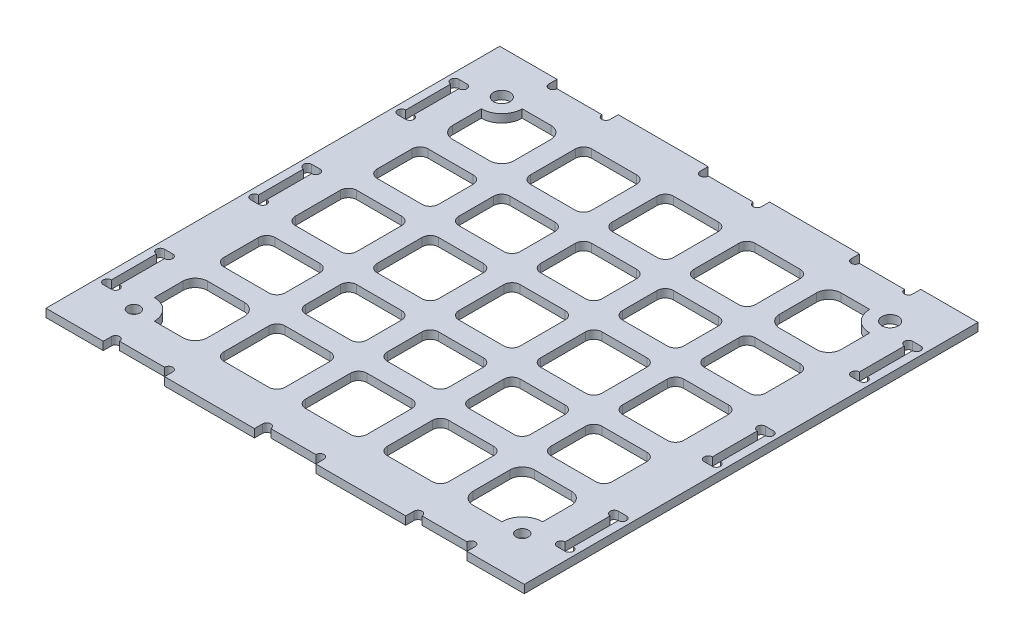
SolidWorks part; units mm, degrees
ref_plane "前视基准面" through (0, 0, 0) normal (0, 0, 1) x (1, 0, 0)
ref_plane "上视基准面" through (0, 0, 0) normal (0, 1, 0) x (1, 0, 0)
ref_plane "右视基准面" through (0, 0, 0) normal (1, 0, 0) x (0, 0, -1)
sketch "草图1" plane through (0, 0, 0) normal (0, 1, 0) x (1, 0, 0)
  line L0 (53, 107) -> (53, 47) construction
  line L1 (0, 0) -> (109, 0)
  line L2 (0, 0) -> (0, 107)
  line L3 (0, 107) -> (109, 107)
  line L4 (109, 0) -> (109, 107)
  line L6 (7, 98.5) -> (102, 98.5) construction
  line L7 (7, 98.5) -> (7, 8.5) construction
  line L8 (7, 8.5) -> (102, 8.5) construction
  line L9 (102, 98.5) -> (102, 8.5) construction
  circle A20 centre (7, 98.5) radius 2
  circle A21 centre (102, 98.5) radius 2
  circle A22 centre (102, 8.5) radius 1.5
  circle A23 centre (7, 8.5) radius 1.5
  dimension "D5" = 107
  dimension "D13" = 4
  dimension "D14" = 4
  dimension "D15" = 3
  dimension "D16" = 3
  dimension "D2" = 109
  dimension "D3" = 60
  dimension "D4" = 53
  dimension "D9" = 90
  dimension "D10" = 95
  dimension "D11" = 8.5
  dimension "D12" = 7
extrude "凸台-拉伸1" add sketch "草图1" along normal blind 2
sketch "草图2" plane through (0, 2, 0) normal (0, 1, 0) x (1, 0, 0)
  line L0 (109, 107) -> (0, 107) construction
  line L5 (0, 0) -> (109, 0) construction
  line L6 (0, 107) -> (0, 0) construction
  line L7 (109, 0) -> (109, 107) construction
  line L9 (10, 107) -> (10, 109)
  line L11 (25, 107) -> (25, 109)
  line L13 (47, 107) -> (47, 109)
  line L15 (62, 107) -> (62, 109)
  line L17 (84, 107) -> (84, 109)
  line L19 (99, 107) -> (99, 109)
  line L20 (0, 53.5) -> (109, 53.5) construction
  line L21 (54.5, 0) -> (54.5, 107) construction
  line L22 (109, 97) -> (111, 97)
  line L48 (0, 97) -> (-2, 97)
  line L49 (10, 107) -> (0, 107)
  line L50 (0, 107) -> (0, 97)
  line L51 (25, 107) -> (47, 107)
  line L52 (62, 107) -> (84, 107)
  line L53 (99, 107) -> (109, 107)
  line L54 (109, 107) -> (109, 97)
  line L67 (10, 109) -> (-2, 109)
  line L68 (-2, 109) -> (-2, 97)
  line L69 (25, 109) -> (47, 109)
  line L70 (62, 109) -> (84, 109)
  line L71 (99, 109) -> (111, 109)
  line L72 (111, 109) -> (111, 97)
  line L81 (109, 82) -> (111, 82) [skipped]
  line L82 (109, 60) -> (111, 60) [skipped]
  line L83 (109, 45) -> (111, 45) [skipped]
  line L84 (109, 23) -> (111, 23) [skipped]
  line L85 (109, 8) -> (111, 8) [skipped]
  line L86 (99, -2) -> (99, -4) [skipped]
  line L87 (84, -2) -> (84, -4) [skipped]
  line L88 (62, -2) -> (62, -4) [skipped]
  line L89 (47, -2) -> (47, -4) [skipped]
  line L90 (25, -2) -> (25, -4) [skipped]
  line L91 (10, -2) -> (10, -4) [skipped]
  line L92 (0, 8) -> (-2, 8) [skipped]
  line L93 (0, 23) -> (-2, 23) [skipped]
  line L94 (0, 45) -> (-2, 45) [skipped]
  line L95 (0, 60) -> (-2, 60) [skipped]
  line L96 (0, 82) -> (-2, 82) [skipped]
  line L97 (111, 46) -> (111, 25)
  line L98 (0, 82) -> (-2, 82)
  line L99 (0, 82) -> (0, 61)
  line L100 (0, 61) -> (-2, 61)
  line L101 (-2, 82) -> (-2, 61)
  line L102 (0, 46) -> (-2, 46)
  line L103 (0, 46) -> (0, 25)
  line L104 (0, 25) -> (-2, 25)
  line L105 (-2, 46) -> (-2, 25)
  line L106 (109, 25) -> (111, 25)
  line L107 (109, 46) -> (109, 25)
  line L108 (109, 46) -> (111, 46)
  line L109 (111, 82) -> (111, 61)
  line L110 (109, 61) -> (111, 61)
  line L111 (109, 82) -> (109, 61)
  line L112 (109, 82) -> (111, 82)
  line L113 (111, -2) -> (111, 10)
  line L114 (99, -2) -> (111, -2)
  line L115 (62, -2) -> (84, -2)
  line L116 (25, -2) -> (47, -2)
  line L117 (-2, -2) -> (-2, 10)
  line L118 (10, -2) -> (-2, -2)
  line L119 (109, 0) -> (109, 10)
  line L120 (99, 0) -> (109, 0)
  line L121 (62, 0) -> (84, 0)
  line L122 (25, 0) -> (47, 0)
  line L123 (0, 0) -> (0, 10)
  line L124 (10, 0) -> (0, 0)
  line L125 (0, 10) -> (-2, 10)
  line L126 (109, 10) -> (111, 10)
  line L127 (99, 0) -> (99, -2)
  line L128 (84, 0) -> (84, -2)
  line L129 (62, 0) -> (62, -2)
  line L130 (47, 0) -> (47, -2)
  line L131 (25, 0) -> (25, -2)
  line L132 (10, 0) -> (10, -2)
  dimension "D2" = 22
  dimension "D3" = 15
  dimension "D4" = 10
  dimension "D5" = 15
  dimension "D6" = 21
  dimension "D7" = 15
  dimension "D8" = 10
  dimension "D9" = 15
  dimension "D10" = 2
  dimension "D12" = 15
  dimension "D13" = 21
  dimension "D11" = 4
extrude "凸台-拉伸2" add sketch "草图2" against normal up to surface (2 mm away) up to face at (102, 0, -7)
sketch "草图4" plane through (0, 2, 0) normal (0, 1, 0) x (1, 0, 0)
  line L0 (25, 107) -> (10, 107) construction
  line L1 (10, 107) -> (12, 107)
  line L2 (17.5, 107) -> (17.5, 0) construction
  line L4 (36, 109) -> (36, -2) construction
  line L5 (0, 53.5) -> (109, 53.5) construction
  line L6 (47, 109) -> (25, 109) construction
  line L8 (54.5, 107) -> (54.5, 0) construction
  line L9 (62, 107) -> (47, 107) construction
  line L11 (25, 107) -> (23, 107)
  line L12 (47, 107) -> (49, 107)
  line L13 (62, 107) -> (60, 107)
  line L14 (84, 107) -> (86, 107)
  line L15 (99, 107) -> (97, 107)
  line L34 (0, 84) -> (0, 82)
  line L35 (0, 61) -> (0, 46) construction
  line L36 (109, 46) -> (109, 61) construction
  line L37 (99, 0) -> (97, 0)
  line L38 (84, 0) -> (86, 0)
  line L39 (62, 0) -> (60, 0)
  line L40 (47, 0) -> (49, 0)
  line L41 (25, 0) -> (23, 0)
  line L42 (10, 0) -> (12, 0)
  line L43 (0, 95) -> (0, 97)
  line L44 (0, 97) -> (0, 82) construction
  line L45 (0, 89.5) -> (109, 89.5) construction
  line L46 (109, 82) -> (109, 97) construction
  line L47 (-2, 71.5) -> (111, 71.5) construction
  line L48 (-2, 82) -> (-2, 61) construction
  line L49 (111, 61) -> (111, 82) construction
  line L50 (0, 59) -> (0, 61)
  line L51 (0, 48) -> (0, 46)
  line L52 (0, 12) -> (0, 10)
  line L53 (0, 23) -> (0, 25)
  line L54 (109, 23) -> (109, 25)
  line L55 (109, 12) -> (109, 10)
  line L56 (109, 48) -> (109, 46)
  line L57 (109, 59) -> (109, 61)
  line L58 (109, 95) -> (109, 97)
  line L59 (109, 84) -> (109, 82)
  line L60 (10, 0) -> (25, 0) construction
  line L61 (25, -2) -> (47, -2) construction
  line L62 (47, 0) -> (62, 0) construction
  arc A0 (10, 107) -> (12, 107) centre (11, 107) ccw
  arc A1 (99, 0) -> (97, 0) centre (98, 0) ccw
  arc A2 (25, 107) -> (23, 107) centre (24, 107) cw
  arc A3 (47, 107) -> (49, 107) centre (48, 107) ccw
  arc A4 (62, 107) -> (60, 107) centre (61, 107) cw
  arc A5 (84, 107) -> (86, 107) centre (85, 107) ccw
  arc A6 (99, 107) -> (97, 107) centre (98, 107) cw
  arc A25 (84, 0) -> (86, 0) centre (85, 0) cw
  arc A26 (62, 0) -> (60, 0) centre (61, 0) ccw
  arc A27 (47, 0) -> (49, 0) centre (48, 0) cw
  arc A28 (25, 0) -> (23, 0) centre (24, 0) ccw
  arc A29 (10, 0) -> (12, 0) centre (11, 0) cw
  arc A30 (0, 97) -> (0, 95) centre (0, 96) cw
  arc A31 (0, 82) -> (0, 84) centre (0, 83) ccw
  arc A32 (0, 61) -> (0, 59) centre (0, 60) cw
  arc A33 (0, 46) -> (0, 48) centre (0, 47) ccw
  arc A34 (0, 25) -> (0, 23) centre (0, 24) cw
  arc A35 (0, 10) -> (0, 12) centre (0, 11) ccw
  arc A36 (109, 10) -> (109, 12) centre (109, 11) cw
  arc A37 (109, 25) -> (109, 23) centre (109, 24) ccw
  arc A38 (109, 46) -> (109, 48) centre (109, 47) cw
  arc A39 (109, 61) -> (109, 59) centre (109, 60) ccw
  arc A40 (109, 82) -> (109, 84) centre (109, 83) cw
  arc A41 (109, 97) -> (109, 95) centre (109, 96) ccw
  dimension "D1" = 1
extrude "切除-拉伸1" cut sketch "草图4" against normal through all
sketch "草图5" plane through (0, 2, 0) normal (0, 1, 0) x (1, 0, 0)
  line L0 (12, 98.5) -> (19, 98.5)
  line L1 (22, 95.5) -> (22, 86.5)
  line L2 (19, 83.5) -> (10, 83.5)
  line L3 (7, 86.5) -> (7, 93.5)
  line L4 (0, 53.5) -> (109, 53.5) construction
  line L5 (0, 59) -> (0, 48) construction
  line L6 (109, 48) -> (109, 59) construction
  line L7 (54.5, 107) -> (54.5, 0) construction
  line L8 (60, 107) -> (49, 107) construction
  line L9 (49, 0) -> (60, 0) construction
  line L22 (102, 86.5) -> (102, 93.5)
  line L23 (90, 83.5) -> (99, 83.5)
  line L24 (87, 95.5) -> (87, 86.5)
  line L25 (97, 98.5) -> (90, 98.5)
  line L26 (97, 8.5) -> (90, 8.5)
  line L27 (87, 11.5) -> (87, 20.5)
  line L28 (90, 23.5) -> (99, 23.5)
  line L29 (102, 20.5) -> (102, 13.5)
  line L30 (7, 20.5) -> (7, 13.5)
  line L31 (19, 23.5) -> (10, 23.5)
  line L32 (22, 11.5) -> (22, 20.5)
  line L33 (12, 8.5) -> (19, 8.5)
  line L34 (80, 46) -> (69, 46)
  line L35 (9, 78.5) -> (20, 78.5)
  line L36 (7, 76.5) -> (7, 68)
  line L37 (9, 66) -> (20, 66)
  line L38 (22, 76.5) -> (22, 68)
  line L39 (9, 61) -> (20, 61)
  line L40 (7, 59) -> (7, 48)
  line L41 (9, 46) -> (20, 46)
  line L42 (22, 59) -> (22, 48)
  line L43 (29, 78.5) -> (40, 78.5)
  line L44 (27, 76.5) -> (27, 68)
  line L45 (29, 66) -> (40, 66)
  line L46 (42, 76.5) -> (42, 68)
  line L47 (29, 98.5) -> (40, 98.5)
  line L48 (27, 96.5) -> (27, 85.5)
  line L49 (29, 83.5) -> (40, 83.5)
  line L50 (42, 96.5) -> (42, 85.5)
  line L51 (49, 98.5) -> (60, 98.5)
  line L52 (47, 96.5) -> (47, 85.5)
  line L53 (49, 83.5) -> (60, 83.5)
  line L54 (62, 96.5) -> (62, 85.5)
  line L55 (49, 78.5) -> (60, 78.5)
  line L56 (47, 76.5) -> (47, 68)
  line L57 (49, 66) -> (60, 66)
  line L58 (62, 76.5) -> (62, 68)
  line L59 (29, 61) -> (40, 61)
  line L60 (27, 59) -> (27, 48)
  line L61 (29, 46) -> (40, 46)
  line L62 (42, 59) -> (42, 48)
  line L63 (49, 61) -> (60, 61)
  line L64 (47, 59) -> (47, 48)
  line L65 (49, 46) -> (60, 46)
  line L66 (62, 59) -> (62, 48)
  line L67 (67, 59) -> (67, 48)
  line L68 (80, 61) -> (69, 61)
  line L69 (82, 59) -> (82, 48)
  line L70 (100, 46) -> (89, 46)
  line L71 (87, 59) -> (87, 48)
  line L72 (100, 61) -> (89, 61)
  line L73 (102, 59) -> (102, 48)
  line L74 (100, 66) -> (89, 66)
  line L75 (87, 76.5) -> (87, 68)
  line L76 (100, 78.5) -> (89, 78.5)
  line L77 (102, 76.5) -> (102, 68)
  line L78 (80, 66) -> (69, 66)
  line L79 (67, 76.5) -> (67, 68)
  line L80 (80, 78.5) -> (69, 78.5)
  line L81 (82, 76.5) -> (82, 68)
  line L82 (80, 83.5) -> (69, 83.5)
  line L83 (67, 96.5) -> (67, 85.5)
  line L84 (80, 98.5) -> (69, 98.5)
  line L85 (82, 96.5) -> (82, 85.5)
  line L86 (102, 30.5) -> (102, 39)
  line L87 (100, 28.5) -> (89, 28.5)
  line L88 (87, 30.5) -> (87, 39)
  line L89 (100, 41) -> (89, 41)
  line L90 (82, 10.5) -> (82, 21.5)
  line L91 (80, 8.5) -> (69, 8.5)
  line L92 (67, 10.5) -> (67, 21.5)
  line L93 (80, 23.5) -> (69, 23.5)
  line L94 (82, 30.5) -> (82, 39)
  line L95 (80, 28.5) -> (69, 28.5)
  line L96 (67, 30.5) -> (67, 39)
  line L97 (80, 41) -> (69, 41)
  line L98 (49, 41) -> (60, 41)
  line L99 (62, 30.5) -> (62, 39)
  line L100 (49, 28.5) -> (60, 28.5)
  line L101 (47, 30.5) -> (47, 39)
  line L102 (49, 23.5) -> (60, 23.5)
  line L103 (62, 10.5) -> (62, 21.5)
  line L104 (49, 8.5) -> (60, 8.5)
  line L105 (47, 10.5) -> (47, 21.5)
  line L106 (29, 23.5) -> (40, 23.5)
  line L107 (42, 10.5) -> (42, 21.5)
  line L108 (29, 8.5) -> (40, 8.5)
  line L109 (27, 10.5) -> (27, 21.5)
  line L110 (29, 41) -> (40, 41)
  line L111 (42, 30.5) -> (42, 39)
  line L112 (29, 28.5) -> (40, 28.5)
  line L113 (27, 30.5) -> (27, 39)
  line L114 (9, 41) -> (20, 41)
  line L115 (22, 30.5) -> (22, 39)
  line L116 (9, 28.5) -> (20, 28.5)
  line L117 (7, 30.5) -> (7, 39)
  arc A0 (7, 93.5) -> (12, 98.5) centre (7, 98.5) ccw
  arc A4 (102, 93.5) -> (97, 98.5) centre (102, 98.5) cw
  arc A5 (102, 13.5) -> (97, 8.5) centre (102, 8.5) ccw
  arc A6 (7, 13.5) -> (12, 8.5) centre (7, 8.5) cw
  arc A7 (19, 98.5) -> (22, 95.5) centre (19, 95.5) cw
  arc A8 (22, 86.5) -> (19, 83.5) centre (19, 86.5) cw
  arc A9 (10, 83.5) -> (7, 86.5) centre (10, 86.5) cw
  arc A10 (22, 11.5) -> (19, 8.5) centre (19, 11.5) cw
  arc A11 (7, 20.5) -> (10, 23.5) centre (10, 20.5) cw
  arc A12 (19, 23.5) -> (22, 20.5) centre (19, 20.5) cw
  arc A13 (99, 23.5) -> (102, 20.5) centre (99, 20.5) cw
  arc A14 (90, 8.5) -> (87, 11.5) centre (90, 11.5) cw
  arc A15 (87, 20.5) -> (90, 23.5) centre (90, 20.5) cw
  arc A16 (87, 95.5) -> (90, 98.5) centre (90, 95.5) cw
  arc A17 (102, 86.5) -> (99, 83.5) centre (99, 86.5) cw
  arc A18 (90, 83.5) -> (87, 86.5) centre (90, 86.5) cw
  arc A19 (9, 61) -> (7, 59) centre (9, 59) ccw
  arc A20 (7, 48) -> (9, 46) centre (9, 48) ccw
  arc A21 (20, 46) -> (22, 48) centre (20, 48) ccw
  arc A22 (20, 61) -> (22, 59) centre (20, 59) cw
  arc A23 (29, 61) -> (27, 59) centre (29, 59) ccw
  arc A24 (27, 48) -> (29, 46) centre (29, 48) ccw
  arc A25 (40, 46) -> (42, 48) centre (40, 48) ccw
  arc A26 (40, 61) -> (42, 59) centre (40, 59) cw
  arc A27 (49, 61) -> (47, 59) centre (49, 59) ccw
  arc A28 (47, 48) -> (49, 46) centre (49, 48) ccw
  arc A29 (60, 46) -> (62, 48) centre (60, 48) ccw
  arc A30 (60, 61) -> (62, 59) centre (60, 59) cw
  arc A31 (60, 66) -> (62, 68) centre (60, 68) ccw
  arc A32 (47, 68) -> (49, 66) centre (49, 68) ccw
  arc A33 (49, 78.5) -> (47, 76.5) centre (49, 76.5) ccw
  arc A34 (60, 78.5) -> (62, 76.5) centre (60, 76.5) cw
  arc A35 (60, 83.5) -> (62, 85.5) centre (60, 85.5) ccw
  arc A36 (60, 98.5) -> (62, 96.5) centre (60, 96.5) cw
  arc A37 (47, 85.5) -> (49, 83.5) centre (49, 85.5) ccw
  arc A38 (49, 98.5) -> (47, 96.5) centre (49, 96.5) ccw
  arc A39 (27, 68) -> (29, 66) centre (29, 68) ccw
  arc A40 (40, 66) -> (42, 68) centre (40, 68) ccw
  arc A41 (40, 78.5) -> (42, 76.5) centre (40, 76.5) cw
  arc A42 (40, 83.5) -> (42, 85.5) centre (40, 85.5) ccw
  arc A43 (40, 98.5) -> (42, 96.5) centre (40, 96.5) cw
  arc A44 (29, 98.5) -> (27, 96.5) centre (29, 96.5) ccw
  arc A45 (27, 85.5) -> (29, 83.5) centre (29, 85.5) ccw
  arc A46 (29, 78.5) -> (27, 76.5) centre (29, 76.5) ccw
  arc A47 (7, 68) -> (9, 66) centre (9, 68) ccw
  arc A48 (20, 66) -> (22, 68) centre (20, 68) ccw
  arc A49 (20, 78.5) -> (22, 76.5) centre (20, 76.5) cw
  arc A50 (9, 78.5) -> (7, 76.5) centre (9, 76.5) ccw
  arc A51 (69, 46) -> (67, 48) centre (69, 48) cw
  arc A52 (69, 61) -> (67, 59) centre (69, 59) ccw
  arc A53 (80, 61) -> (82, 59) centre (80, 59) cw
  arc A54 (82, 48) -> (80, 46) centre (80, 48) cw
  arc A55 (89, 46) -> (87, 48) centre (89, 48) cw
  arc A56 (89, 61) -> (87, 59) centre (89, 59) ccw
  arc A57 (100, 61) -> (102, 59) centre (100, 59) cw
  arc A58 (102, 48) -> (100, 46) centre (100, 48) cw
  arc A59 (89, 66) -> (87, 68) centre (89, 68) cw
  arc A60 (89, 78.5) -> (87, 76.5) centre (89, 76.5) ccw
  arc A61 (102, 68) -> (100, 66) centre (100, 68) cw
  arc A62 (100, 78.5) -> (102, 76.5) centre (100, 76.5) cw
  arc A63 (69, 66) -> (67, 68) centre (69, 68) cw
  arc A64 (69, 78.5) -> (67, 76.5) centre (69, 76.5) ccw
  arc A65 (82, 68) -> (80, 66) centre (80, 68) cw
  arc A66 (80, 78.5) -> (82, 76.5) centre (80, 76.5) cw
  arc A67 (69, 83.5) -> (67, 85.5) centre (69, 85.5) cw
  arc A68 (69, 98.5) -> (67, 96.5) centre (69, 96.5) ccw
  arc A69 (80, 98.5) -> (82, 96.5) centre (80, 96.5) cw
  arc A70 (82, 85.5) -> (80, 83.5) centre (80, 85.5) cw
  arc A71 (102, 39) -> (100, 41) centre (100, 39) ccw
  arc A72 (100, 28.5) -> (102, 30.5) centre (100, 30.5) ccw
  arc A73 (89, 28.5) -> (87, 30.5) centre (89, 30.5) cw
  arc A74 (89, 41) -> (87, 39) centre (89, 39) ccw
  arc A75 (82, 21.5) -> (80, 23.5) centre (80, 21.5) ccw
  arc A76 (80, 8.5) -> (82, 10.5) centre (80, 10.5) ccw
  arc A77 (69, 8.5) -> (67, 10.5) centre (69, 10.5) cw
  arc A78 (69, 23.5) -> (67, 21.5) centre (69, 21.5) ccw
  arc A79 (82, 39) -> (80, 41) centre (80, 39) ccw
  arc A80 (80, 28.5) -> (82, 30.5) centre (80, 30.5) ccw
  arc A81 (69, 28.5) -> (67, 30.5) centre (69, 30.5) cw
  arc A82 (69, 41) -> (67, 39) centre (69, 39) ccw
  arc A83 (60, 41) -> (62, 39) centre (60, 39) cw
  arc A84 (60, 28.5) -> (62, 30.5) centre (60, 30.5) ccw
  arc A85 (47, 39) -> (49, 41) centre (49, 39) cw
  arc A86 (49, 28.5) -> (47, 30.5) centre (49, 30.5) cw
  arc A87 (60, 23.5) -> (62, 21.5) centre (60, 21.5) cw
  arc A88 (60, 8.5) -> (62, 10.5) centre (60, 10.5) ccw
  arc A89 (47, 21.5) -> (49, 23.5) centre (49, 21.5) cw
  arc A90 (49, 8.5) -> (47, 10.5) centre (49, 10.5) cw
  arc A91 (40, 23.5) -> (42, 21.5) centre (40, 21.5) cw
  arc A92 (40, 8.5) -> (42, 10.5) centre (40, 10.5) ccw
  arc A93 (29, 8.5) -> (27, 10.5) centre (29, 10.5) cw
  arc A94 (27, 21.5) -> (29, 23.5) centre (29, 21.5) cw
  arc A95 (40, 41) -> (42, 39) centre (40, 39) cw
  arc A96 (40, 28.5) -> (42, 30.5) centre (40, 30.5) ccw
  arc A97 (27, 39) -> (29, 41) centre (29, 39) cw
  arc A98 (29, 28.5) -> (27, 30.5) centre (29, 30.5) cw
  arc A99 (20, 41) -> (22, 39) centre (20, 39) cw
  arc A100 (20, 28.5) -> (22, 30.5) centre (20, 30.5) ccw
  arc A101 (7, 39) -> (9, 41) centre (9, 39) cw
  arc A102 (9, 28.5) -> (7, 30.5) centre (9, 30.5) cw
  point P39 (22, 98.5)
  point P43 (22, 83.5)
  point P46 (7, 83.5)
  point P49 (22, 8.5)
  point P52 (7, 23.5)
  point P55 (22, 23.5)
  point P58 (102, 23.5)
  point P61 (87, 8.5)
  point P64 (87, 23.5)
  point P67 (87, 98.5)
  point P70 (102, 83.5)
  point P73 (87, 83.5)
  point P108 (7, 61)
  point P111 (7, 46)
  point P114 (22, 46)
  point P117 (22, 61)
  point P124 (42, 46)
  point P127 (42, 61)
  point P138 (62, 66)
  point P141 (47, 66)
  point P148 (62, 83.5)
  point P151 (62, 98.5)
  point P154 (47, 83.5)
  point P157 (47, 98.5)
  point P160 (27, 66)
  point P163 (42, 66)
  point P166 (42, 78.5)
  point P169 (42, 83.5)
  point P172 (42, 98.5)
  point P175 (27, 98.5)
  point P178 (27, 83.5)
  point P183 (7, 66)
  point P186 (22, 66)
  point P189 (22, 78.5)
  point P192 (7, 78.5)
  dimension "D1" = 5
  dimension "D4" = 3
  dimension "D5" = 3
  dimension "D14" = 2
  dimension "D2" = 10
  dimension "D3" = 10
  dimension "D6" = 5
  dimension "D7" = 5
  dimension "D8" = 15
  dimension "D9" = 5
  dimension "D10" = 15
  dimension "D11" = 12.5
  dimension "D12" = 5
  dimension "D13" = 15
extrude "切除-拉伸2" cut sketch "草图5" against normal through all
sketch "草图6" plane through (0, 2, 0) normal (0, 1, 0) x (1, 0, 0)
  line L0 (-2, 95) -> (-2, 84)
  line L2 (-2, 82) -> (-2, 61) construction
  line L3 (-2, 97) -> (-2, 109)
  line L4 (-2, 59) -> (-2, 48)
  line L5 (-2, 23) -> (-2, 12)
  line L6 (-2, 82) -> (-2, 61)
  line L7 (-2, 46) -> (-2, 25)
  line L8 (-2, 10) -> (-2, -2)
  line L9 (-2, -2) -> (-4, -2)
  line L10 (-4, -2) -> (-4, 109)
  line L11 (-4, 109) -> (-2, 109)
  line L12 (54.5, 107) -> (54.5, 0) construction
  line L13 (60, 107) -> (49, 107) construction
  line L14 (49, 0) -> (60, 0) construction
  line L15 (113, 109) -> (111, 109)
  line L16 (113, -2) -> (113, 109)
  line L17 (111, -2) -> (113, -2)
  line L18 (111, 10) -> (111, -2)
  line L19 (111, 46) -> (111, 25)
  line L20 (111, 82) -> (111, 61)
  line L21 (111, 23) -> (111, 12)
  line L22 (111, 59) -> (111, 48)
  line L23 (111, 97) -> (111, 109)
  line L24 (111, 95) -> (111, 84)
  arc A0 (-2, 97) -> (-2, 95) centre (-2, 96) ccw
  arc A1 (-2, 84) -> (-2, 82) centre (-2, 83) ccw
  arc A2 (-2, 61) -> (-2, 59) centre (-2, 60) ccw
  arc A3 (-2, 48) -> (-2, 46) centre (-2, 47) ccw
  arc A4 (-2, 25) -> (-2, 23) centre (-2, 24) ccw
  arc A5 (-2, 12) -> (-2, 10) centre (-2, 11) ccw
  arc A6 (111, 12) -> (111, 10) centre (111, 11) cw
  arc A7 (111, 25) -> (111, 23) centre (111, 24) cw
  arc A8 (111, 48) -> (111, 46) centre (111, 47) cw
  arc A9 (111, 61) -> (111, 59) centre (111, 60) cw
  arc A10 (111, 84) -> (111, 82) centre (111, 83) cw
  arc A11 (111, 97) -> (111, 95) centre (111, 96) cw
  dimension "D1" = 1
  dimension "D3" = 2
  dimension "D2" = 3
extrude "凸台-拉伸4" add sketch "草图6" against normal up to surface (2 mm away) up to face at (74.5, 0, -53.5)
